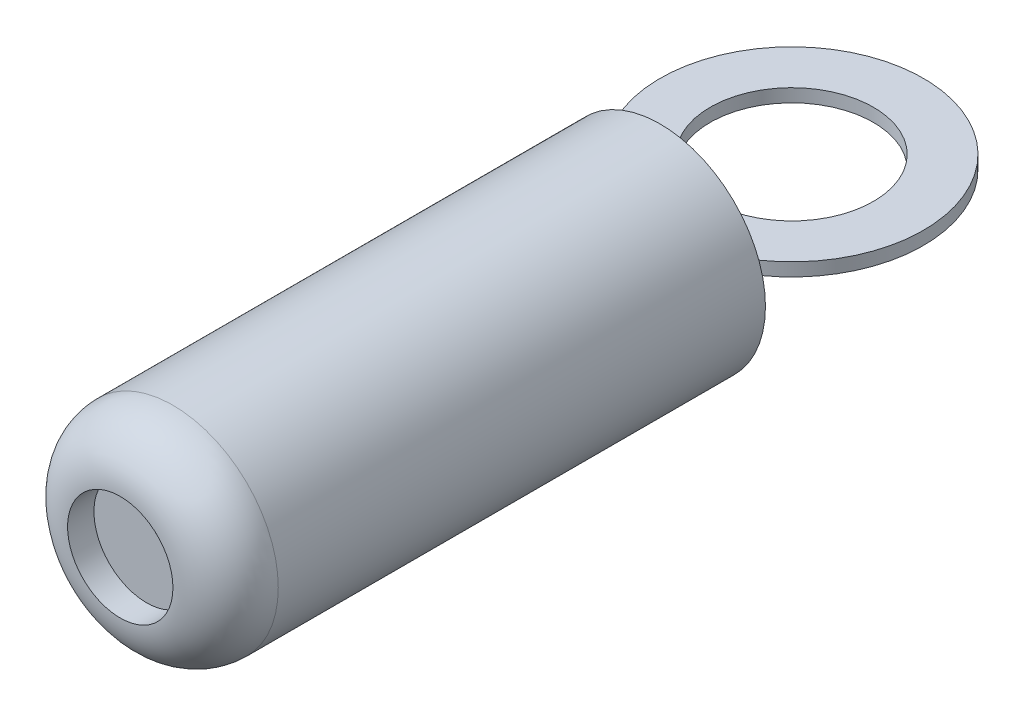
SolidWorks part; units mm, degrees
ref_plane "正面" through (0, 0, 0) normal (0, 0, 1) x (1, 0, 0)
ref_plane "平面" through (0, 0, 0) normal (0, 1, 0) x (1, 0, 0)
ref_plane "右側面" through (0, 0, 0) normal (1, 0, 0) x (0, 0, -1)
sketch "ｽｹｯﾁ8" plane through (0, 0, 0) normal (0, 0, 1) x (1, 0, 0)
  circle A0 centre (0, 0) radius 4
  dimension "D1" = 8
extrude "ﾎﾞｽ - 押し出し4" add sketch "ｽｹｯﾁ8" along normal blind 20.5
sketch "ｽｹｯﾁ10" plane through (0, 0, 0) normal (0, 1, 0) x (1, 0, 0)
  line L0 (0, 0) -> (0, 5) construction
  circle A0 centre (0, 5) radius 5
  circle A1 centre (0, 5) radius 3.1
  dimension "D2" = 6.2
  dimension "D1" = 5
extrude "ﾎﾞｽ - 押し出し5" add sketch "ｽｹｯﾁ10" along normal blind 0.5 separate body
fillet "ﾌｨﾚｯﾄ1" radius 2 1 edges at (4, 0, 20.5)
sketch "ｽｹｯﾁ11" plane through (0, 0, 20.5) normal (0, 0, 1) x (1, 0, 0)
  circle A0 centre (0, 0) radius 2
extrude "ｶｯﾄ - 押し出し1" cut sketch "ｽｹｯﾁ11" against normal blind 1
